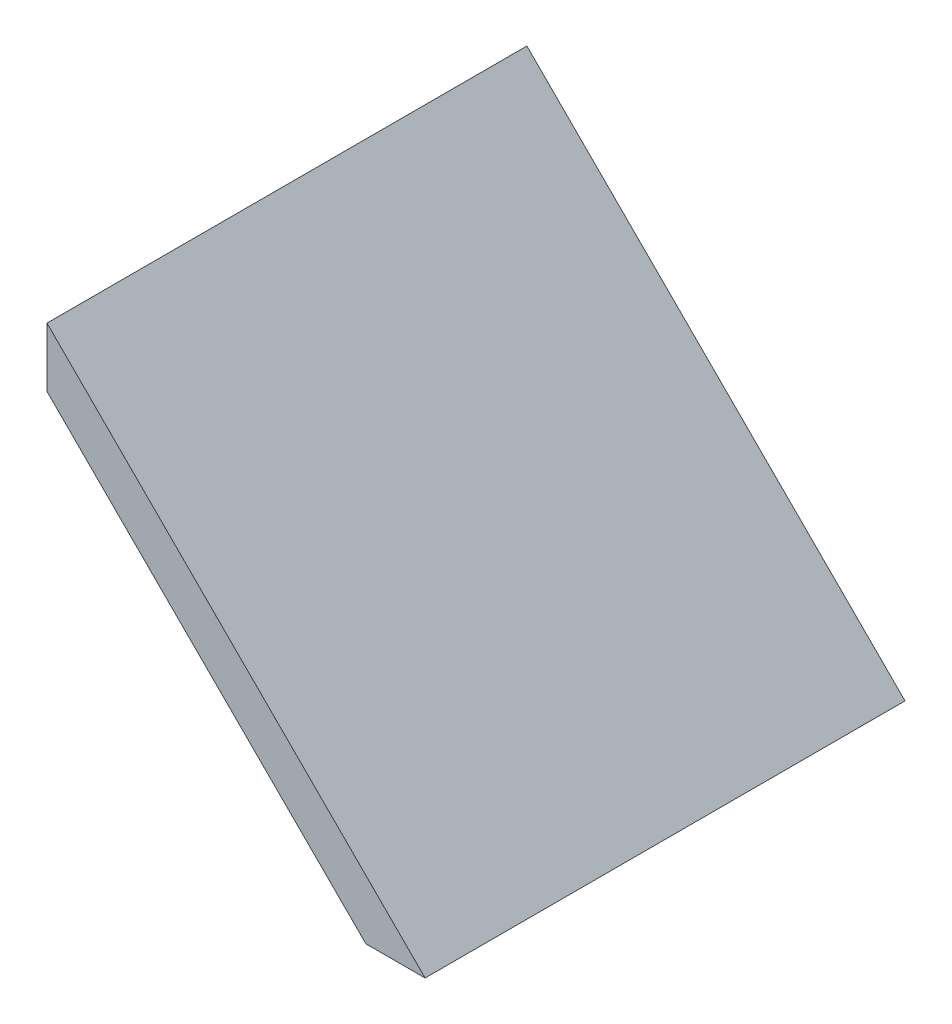
SolidWorks part; units mm, degrees
ref_plane "Front Plane" through (0, 0, 0) normal (0, 0, 1) x (1, 0, 0)
ref_plane "Top Plane" through (0, 0, 0) normal (0, 1, 0) x (1, 0, 0)
ref_plane "Right Plane" through (0, 0, 0) normal (1, 0, 0) x (0, 0, -1)
sketch "Sketch1" plane through (0, 0, 0) normal (0, 0, 1) x (1, 0, 0)
  line L0 (114.3, 0) -> (0, 114.3)
  line L1 (0, 114.3) -> (0, 135.5132)
  line L2 (0, 135.5132) -> (135.5132, 0)
  line L3 (135.5132, 0) -> (114.3, 0)
  point P5 (0, 0)
  point P7 (-17.9866, 137.3949)
  dimension "D1" = 114.3
  dimension "D2" = 114.3
  dimension "D3" = 15
extrude "Boss-Extrude1" add sketch "Sketch1" along normal blind 172
